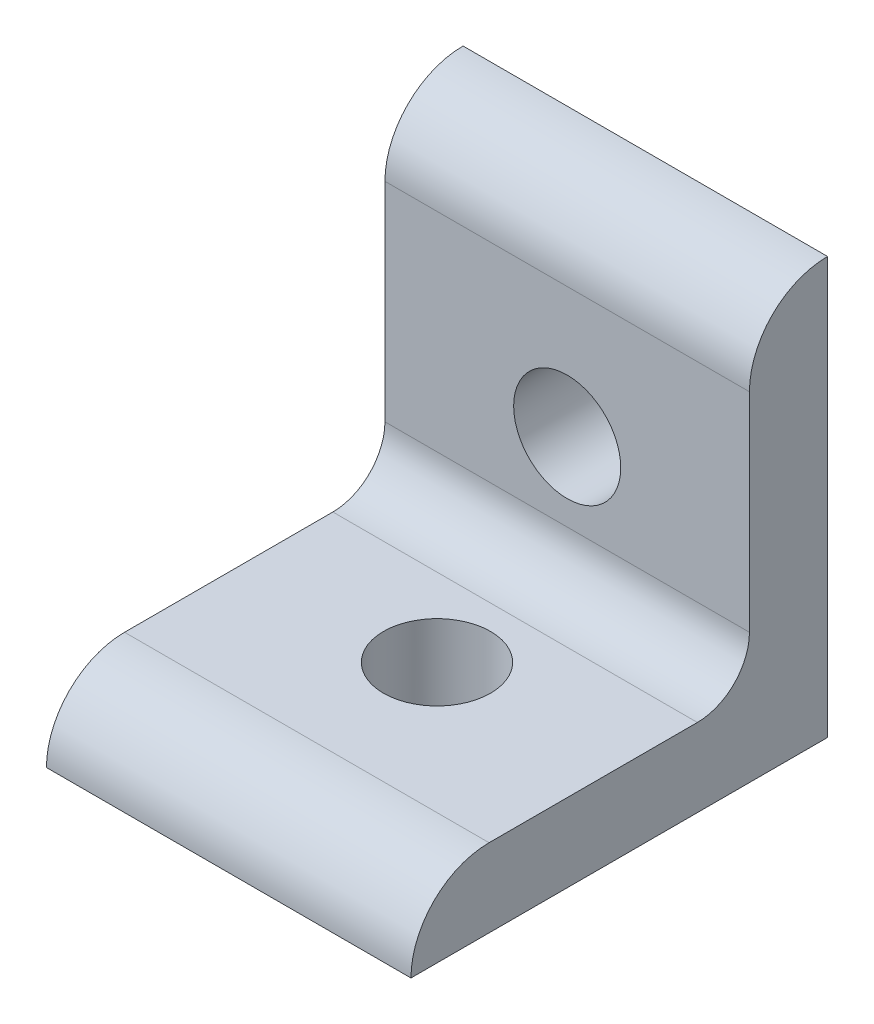
SolidWorks part; units mm, degrees
ref_plane "Front"
ref_plane "Top" through (0, 0, 0) normal (0, 1, 0) x (1, 0, 0)
ref_plane "Right" through (0, 0, 0) normal (1, 0, 0) x (0, 0, -1)
sketch "Sketch1" plane through (0, 0, 0) normal (1, 0, 0) x (0, 0, -1)
  line L0 (-4.7625, 7.9375) -> (-4.7625, 20.6375)
  line L1 (-20.6375, 4.7625) -> (-7.9375, 4.7625)
  line L6 (0, 0) -> (0, 25.4)
  line L7 (-25.4, 0) -> (0, 0)
  arc A0 (-7.9375, 4.7625) -> (-4.7625, 7.9375) centre (-7.9375, 7.9375) ccw
  arc A1 (0, 25.4) -> (-4.7625, 20.6375) centre (0, 20.6375) ccw
  arc A2 (-20.6375, 4.7625) -> (-25.4, 0) centre (-20.6375, 0) ccw
  dimension "InnerRadius" = 3.175
  dimension "LengthZ" = 25.4
  dimension "HeightY" = 25.4
  dimension "Thick" = 4.7625
extrude "Base Extrude" add sketch "Sketch1" against normal mid plane 22.225
sketch "Sketch2" plane through (0, 0, 0) normal (0, -1, 0) x (1, 0, 0)
  line L0 (-11.1125, 0) -> (11.1125, 0) construction
  line L1 (-11.1125, 25.4) -> (-11.1125, 0) construction
  circle A1 centre (0, 12.7) radius 3.2639
  dimension "Hole1Diam" = 6.5278
  dimension "Hole1Z" = 12.7
  dimension "Hole1X" = 11.1125
extrude "Hole1" cut sketch "Sketch2" against normal through all
pattern_linear "Hole1 Pattern" [suppressed]
sketch "Sketch3" plane through (0, 0, 0) normal (0, 0, -1) x (-1, 0, 0)
  line L0 (11.1125, 0) -> (-11.1125, 0) construction
  line L1 (11.1125, 0) -> (11.1125, 25.4) construction
  circle A0 centre (0, 12.7) radius 3.2639
  dimension "Hole2Diam" = 6.5278
  dimension "Hole2Y" = 12.7
  dimension "Hole2X" = 11.1125
extrude "Hole2" cut sketch "Sketch3" against normal through all
pattern_linear "Hole2 Pattern" [suppressed]
sketch "Sketch4" plane through (0, 0, 0) normal (0, 0, -1) x (-1, 0, 0)
  line L0 (11.1125, 25.4) -> (-7.9375, 25.4)
  line L1 (11.1125, 25.4) -> (-11.1125, 25.4) construction
  line L2 (-7.9375, 25.4) -> (11.1125, -38.1)
  line L3 (11.1125, 0) -> (11.1125, 25.4) construction
  line L4 (11.1125, -38.1) -> (11.1125, 25.4)
  dimension "Corner1X" = 19.05
  dimension "D2" = 63.5
extrude "Corner Cut 1" [suppressed] cut sketch "Sketch4" against normal through all
sketch "Sketch5" plane through (0, 0, 0) normal (0, 0, -1) x (-1, 0, 0)
  line L0 (7.9375, 25.4) -> (-11.1125, 25.4)
  line L1 (11.1125, 25.4) -> (-11.1125, 25.4) construction
  line L2 (-11.1125, 25.4) -> (-11.1125, -38.1)
  line L3 (-11.1125, 0) -> (-11.1125, 25.4) construction
  line L4 (-11.1125, -38.1) -> (7.9375, 25.4)
  dimension "Corner2X" = 19.05
  dimension "D2" = 63.5
extrude "Corner Cut 2" [suppressed] cut sketch "Sketch5" against normal through all
